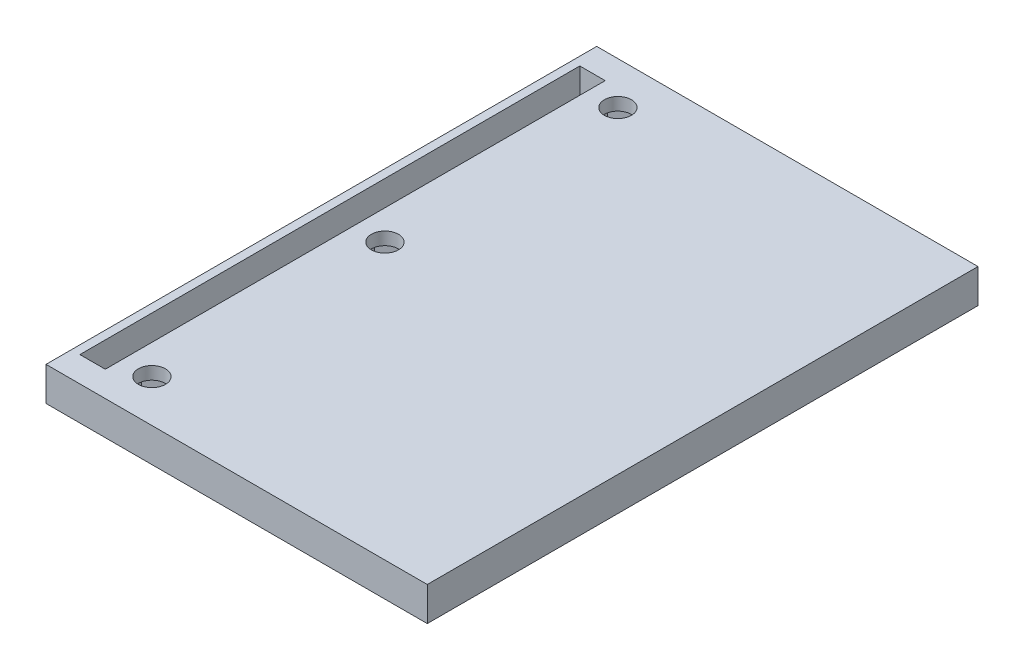
SolidWorks part; units mm, degrees
ref_plane "Front Plane" through (0, 0, 0) normal (0, 0, 1) x (1, 0, 0)
ref_plane "Top Plane" through (0, 0, 0) normal (0, 1, 0) x (1, 0, 0)
ref_plane "Right Plane" through (0, 0, 0) normal (1, 0, 0) x (0, 0, -1)
sketch "Sketch1" plane through (0, 0, 0) normal (0, 1, 0) x (1, 0, 0)
  line L0 (-15, 18.9287) -> (-15, -18.9287) construction
  line L1 (-22.5, 32.5) -> (22.5, 32.5)
  line L2 (-22.5, 32.5) -> (-22.5, -32.5)
  line L3 (-22.5, -32.5) -> (22.5, -32.5)
  line L4 (22.5, 32.5) -> (22.5, -32.5)
  line L5 (-22.5, 32.5) -> (22.5, -32.5) construction
  line L6 (-22.5, -32.5) -> (22.5, 32.5) construction
  line L7 (0, 0) -> (-31.4625, 0) construction
  line L9 (-21.5, 29.5) -> (-18.5, 29.5)
  line L10 (-21.5, 29.5) -> (-21.5, -29.5)
  line L11 (-21.5, -29.5) -> (-18.5, -29.5)
  line L12 (-18.5, 29.5) -> (-18.5, -29.5)
  line L13 (-21.5, 29.5) -> (-18.5, -29.5) construction
  line L14 (-21.5, -29.5) -> (-18.5, 29.5) construction
  circle A0 centre (-15, 27.5) radius 1.6
  circle A1 centre (-15, 0) radius 1.6
  circle A2 centre (-15, -27.5) radius 1.6
  point P0 (0, 0)
  point P14 (-15, 0)
  point P18 (-20, 0)
  dimension "D4" = 3.2
  dimension "D1" = 65
  dimension "D2" = 45
  dimension "D3" = 15
  dimension "D5" = 5
  dimension "D6" = 3
  dimension "D7" = 59
  dimension "D8" = 20
extrude "Boss-Extrude1" add sketch "Sketch1" along normal mid plane 4
sketch "Sketch4" plane through (0, -2, 0) normal (0, -1, 0) x (1, 0, 0)
  line L0 (0, 0) -> (-7.0574, 0) construction
  line L1 (-15, -3.3198) -> (-12.125, -1.6599)
  line L2 (-12.125, -1.6599) -> (-12.125, 1.6599)
  line L3 (-12.125, 1.6599) -> (-15, 3.3198)
  line L4 (-15, 3.3198) -> (-17.875, 1.6599)
  line L5 (-17.875, 1.6599) -> (-17.875, -1.6599)
  line L6 (-17.875, -1.6599) -> (-15, -3.3198)
  line L7 (-17.875, -25.8401) -> (-15, -24.1802)
  line L8 (-15, 24.1802) -> (-12.125, 25.8401)
  line L9 (-12.125, 25.8401) -> (-12.125, 29.1599)
  line L10 (-12.125, 29.1599) -> (-15, 30.8198)
  line L11 (-15, 30.8198) -> (-17.875, 29.1599)
  line L12 (-17.875, 29.1599) -> (-17.875, 25.8401)
  line L13 (-17.875, 25.8401) -> (-15, 24.1802)
  line L14 (-17.875, -29.1599) -> (-17.875, -25.8401)
  line L15 (-15, -30.8198) -> (-17.875, -29.1599)
  line L16 (-12.125, -29.1599) -> (-15, -30.8198)
  line L17 (-12.125, -25.8401) -> (-12.125, -29.1599)
  line L18 (-15, -24.1802) -> (-12.125, -25.8401)
  circle A0 centre (-15, 0) radius 2.875 construction
  circle A1 centre (-15, 27.5) radius 2.875 construction
  dimension "D1" = 5.75
extrude "Cut-Extrude1" cut sketch "Sketch4" against normal blind 2.5
